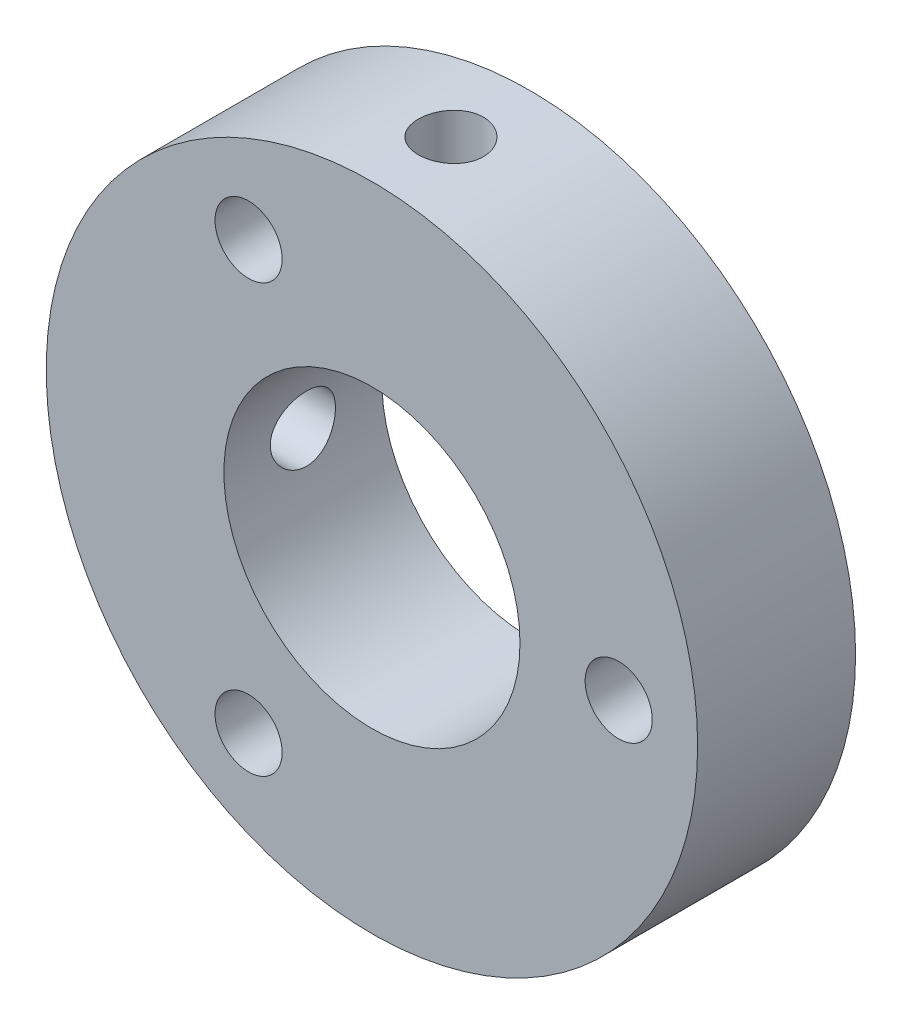
SolidWorks part; units mm, degrees
material "Сплав 2024"
ref_plane "Спереди" through (0, 0, 0) normal (0, 0, 1) x (1, 0, 0)
ref_plane "Сверху" through (0, 0, 0) normal (0, 1, 0) x (1, 0, 0)
ref_plane "Справа" through (0, 0, 0) normal (1, 0, 0) x (0, 0, -1)
sketch "Эскиз1" plane through (0, 0, 0) normal (0, 0, 1) x (1, 0, 0)
  circle A0 centre (0, 0) radius 16.5
  circle A1 centre (0, 0) radius 7.5
  dimension "D1" = 33
  dimension "D2" = 15
extrude "Бобышка-Вытянуть1" add sketch "Эскиз1" along normal blind 8
sketch "Эскиз2" plane through (0, 0, 8) normal (0, 0, 1) x (1, 0, 0)
  line L0 (0, 0) -> (20.3112, 0) construction
  line L1 (0, 0) -> (-10.9456, 18.9584) construction
  line L2 (0, 0) -> (-9.5861, -16.6035) construction
  circle A0 centre (0, 0) radius 12.5 construction
  point P3 (-6.25, 10.8253)
  point P7 (12.5, 0)
  point P8 (-6.25, -10.8253)
  dimension "D1" = 25
  dimension "D2" = 120
  dimension "D3" = 120
hole_wizard "Отверстие с зазором M31" positions "Эскиз4" profile "Эскиз3" hole size "M3" standard "Ansi Metric" end condition through all
sketch "Эскиз4" plane through (0, 0, 8) normal (0, 0, 1) x (1, 0, 0)
  point P0 (-6.25, 10.8253)
  point P3 (12.5, 0)
  point P6 (-6.25, -10.8253)
sketch "Эскиз3" plane through (-6.25, 10.8253, 8) normal (1, 0, 0) x (0, -1, 0)
  line L0 (0, 0) -> (0, 8)
  line L1 (0, 8) -> (1.7, 8)
  line L2 (1.7, 8) -> (1.7, 0)
  line L5 (1.7, 0) -> (0, 0)
  line L11 (0, -6.35) -> (0, 107.95) construction
  dimension "Диаметр сквозного отверстия" = 3.4
  dimension "Глубина сквозного отверстия" = 8
ref_plane "Плоскость1" through (-16.5, 0, 0) normal (-1, 0, 0) x (0, 0, 1)
sketch "Эскиз5" plane through (-16.5, 0, 0) normal (-1, 0, 0) x (0, 0, 1)
  line L0 (4, 16.5) -> (4, -16.5) construction
  line L1 (8, 16.5) -> (0, 16.5) construction
  line L2 (0, -16.5) -> (8, -16.5) construction
  line L3 (0, 0) -> (8, 0) construction
  line L4 (8, -16.5) -> (8, 16.5) construction
hole_wizard "Отверстие обработанное метчиком M4x0.71" positions "Эскиз7" profile "Эскиз6" tap size "M4x0.7" standard "Ansi Metric"
sketch "Эскиз7" plane through (-16.5, 0, 0) normal (-1, 0, 0) x (0, 0, 1)
  line L0 (4, 16.5) -> (4, -16.5) construction
  point P0 (4, 0)
sketch "Эскиз6" plane through (-16.5, 0, 4) normal (0, 1, 0) x (0, 0, 1)
  line L0 (0, 0) -> (0, 9)
  line L1 (0, 9) -> (1.65, 9)
  line L2 (1.65, 9) -> (1.65, 0)
  line L5 (1.65, 0) -> (0, 0)
  line L11 (0, -6.35) -> (0, 107.95) construction
  dimension "Диаметр проходного сверла" = 3.3
  dimension "Глубина проходного сверла" = 9
cosmetic thread "Отверстие резьбы1" parameters "D2"=4
ref_plane "Плоскость2" through (0, 16.5, 0) normal (0, 1, 0) x (0, 0, 1)
sketch "Эскиз8" plane through (0, 16.5, 0) normal (0, 1, 0) x (0, 0, 1)
  line L0 (4, 16.5) -> (4, -16.5) construction
  line L1 (8, 16.5) -> (0, 16.5) construction
  line L2 (-5.5, -16.5) -> (5.5, -16.5) construction
  line L3 (8, 0) -> (0, 0) construction
  line L4 (8, -16.5) -> (8, 16.5) construction
  line L5 (0, 16.5) -> (0, -16.5) construction
hole_wizard "Отверстие обработанное метчиком M4x0.72" positions "Эскиз10" profile "Эскиз9" tap size "M4x0.7" standard "Ansi Metric"
sketch "Эскиз10" plane through (0, 16.5, 0) normal (0, 1, 0) x (0, 0, 1)
  line L0 (4, 16.5) -> (4, -16.5) construction
  point P0 (4, 0)
sketch "Эскиз9" plane through (0, 16.5, 4) normal (1, 0, 0) x (0, 0, 1)
  line L0 (0, 0) -> (0, 9)
  line L1 (0, 9) -> (1.65, 9)
  line L2 (1.65, 9) -> (1.65, 0)
  line L5 (1.65, 0) -> (0, 0)
  line L11 (0, -6.35) -> (0, 107.95) construction
  dimension "Диаметр проходного сверла" = 3.3
  dimension "Глубина проходного сверла" = 9
cosmetic thread "Отверстие резьбы2" parameters "D2"=4
sketch "Эскиз11" plane through (0, 0, 8) normal (0, 0, 1) x (1, 0, 0)
  line L0 (-16.5, 11.7432) -> (-16.5, -16.5) construction
  line L1 (-16.5, -16.5) -> (14.9708, -16.5) construction
  circle A0 centre (0, 0) radius 16.5 construction
